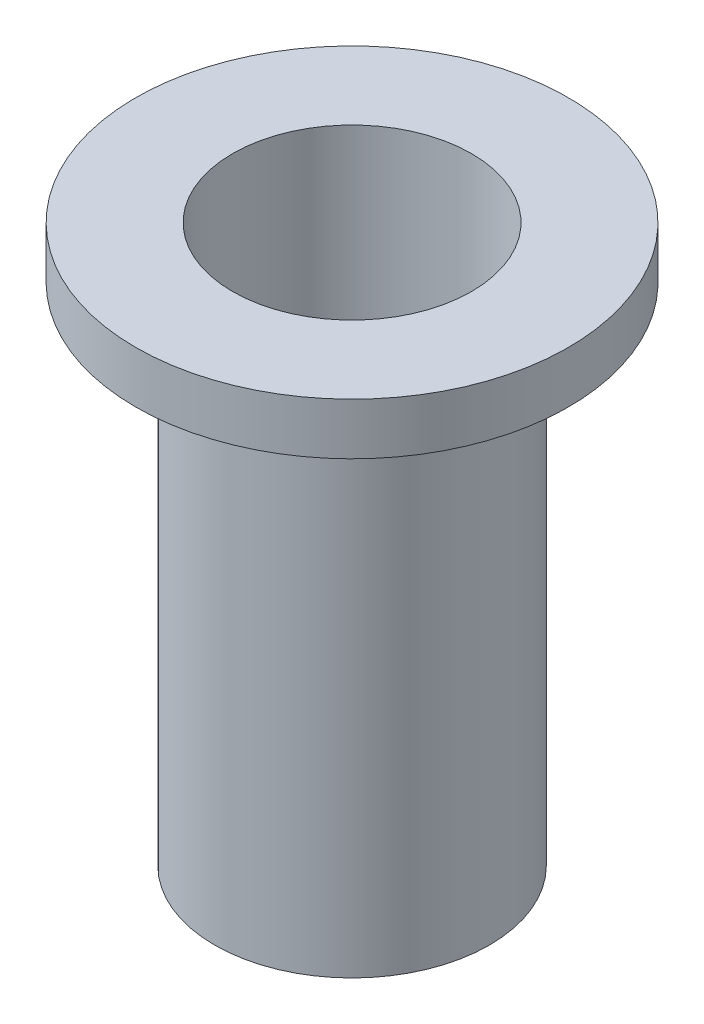
SolidWorks part; units mm, degrees
material "AISI 304"
ref_plane "Front Plane" through (0, 0, 0) normal (0, 0, 1) x (1, 0, 0)
ref_plane "Top Plane" through (0, 0, 0) normal (0, 1, 0) x (1, 0, 0)
ref_plane "Right Plane" through (0, 0, 0) normal (1, 0, 0) x (0, 0, -1)
sketch "Sketch1" plane through (0, 0, 0) normal (0, 1, 0) x (1, 0, 0)
  circle A0 centre (0, 0) radius 11.049
  circle A1 centre (0, 0) radius 12.7
  dimension "D1" = 22.098
  dimension "D2" = 25.4
extrude "Boss-Extrude1" add sketch "Sketch1" along normal blind 46.736
sketch "Sketch2" plane through (0, 46.736, 0) normal (0, 1, 0) x (1, 0, 0)
  circle A0 centre (0, 0) radius 20.0025
  circle A1 centre (0, 0) radius 11.049
  dimension "D1" = 40.005
extrude "Boss-Extrude2" add sketch "Sketch2" along normal blind 4.7752
